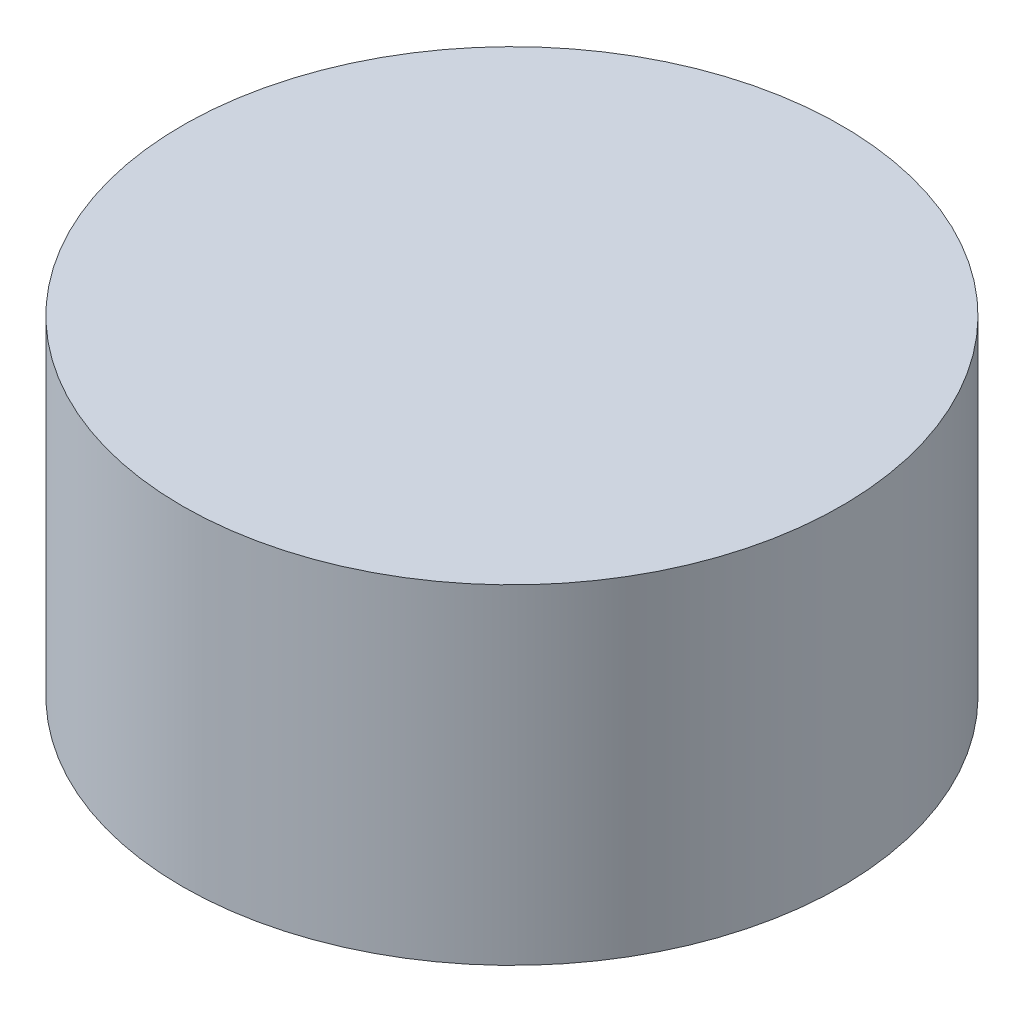
SolidWorks part; units mm, degrees
material "Miedź"
ref_plane "Płaszczyzna przednia" through (0, 0, 0) normal (0, 0, 1) x (1, 0, 0)
ref_plane "Płaszczyzna górna" through (0, 0, 0) normal (0, 1, 0) x (1, 0, 0)
ref_plane "Płaszczyzna prawa" through (0, 0, 0) normal (1, 0, 0) x (0, 0, -1)
sketch "Szkic1" plane through (0, 0, 0) normal (0, 1, 0) x (1, 0, 0)
  line L0 (-61.0765, 17.9546) -> (45.7753, 41.4402)
  line L1 (-50, 0) -> (50, 0)
  line L2 (0, 50) -> (0, -50)
  line L3 (61.0765, 17.9546) -> (-45.7753, 41.4402)
  line L4 (-61.0765, -17.9546) -> (45.7753, -41.4402)
  line L5 (61.0765, -17.9546) -> (-45.7753, -41.4402)
  line L6 (34.2973, 52.5744) -> (-2.1147, -61.4701)
  line L7 (-34.2973, 52.5744) -> (2.1147, -61.4701)
  line L8 (34.2973, -52.5744) -> (-2.1147, 61.4701)
  line L9 (-34.2973, -52.5744) -> (2.1147, 61.4701)
  circle A0 centre (0, 0) radius 50
  circle A1 centre (0, 0) radius 30
  circle A2 centre (0, 0) radius 10
  ellipse E0 centre (0, 0) end of major axis (0, 50) minor radius 10
  ellipse E1 centre (0, 0) end of major axis (0, -50) minor radius 30
  ellipse E2 centre (0, 0) end of major axis (50, 0) minor radius 30
  point P5 (-25.7248, 25.7248)
  point P20 (-8.0582, 29.6078)
  point P34 (25.7248, -25.7248)
  point P39 (8.0582, -29.6078)
  point P41 (25.7248, 25.7248)
  dimension "D1" = 100
  dimension "D2" = 60
  dimension "D3" = 20
extrude "Dodanie-wyciągnięcie1" add sketch "Szkic1" along normal blind 10 contours L1 A2 L2 | L2 A2 L1 | L1 A2 L2 | L2 A2 L1 | L9 | L7 | L0 | L6
